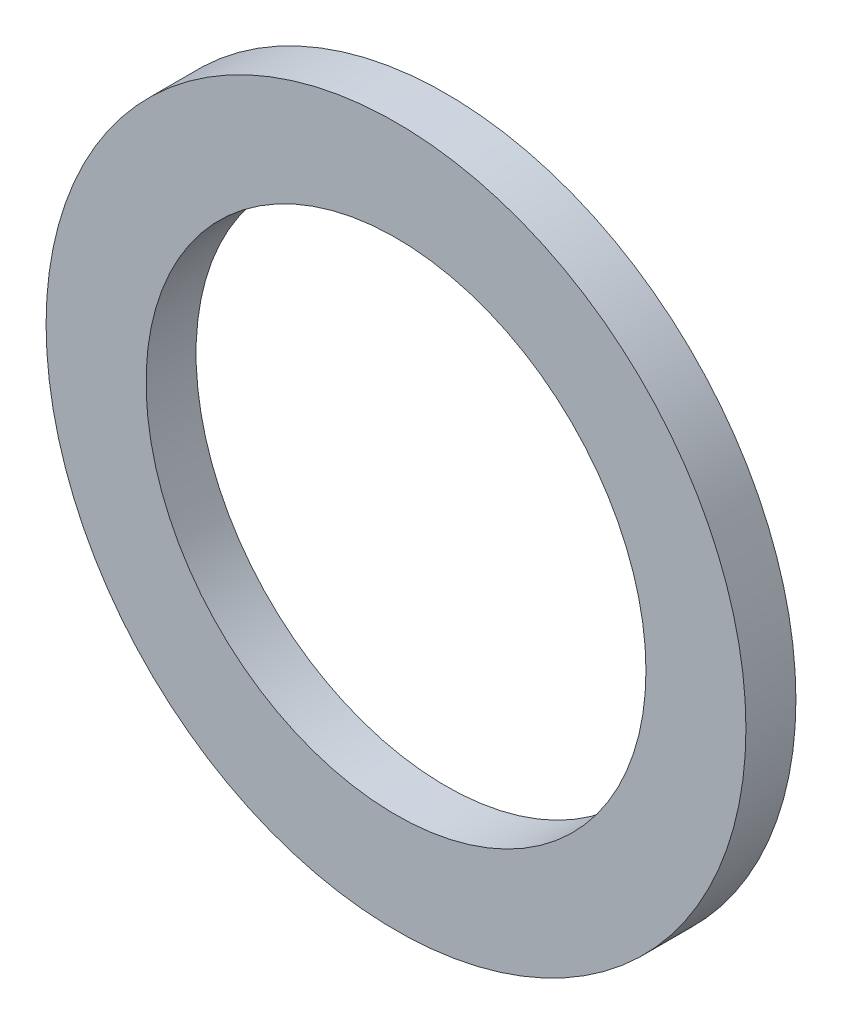
SolidWorks part; units mm, degrees
ref_plane "前视基准面" through (0, 0, 0) normal (0, 0, 1) x (1, 0, 0)
ref_plane "上视基准面" through (0, 0, 0) normal (0, 1, 0) x (1, 0, 0)
ref_plane "右视基准面" through (0, 0, 0) normal (1, 0, 0) x (0, 0, -1)
sketch "草图1" plane through (0, 0, 0) normal (0, 0, 1) x (1, 0, 0)
  circle A0 centre (0, 0) radius 25
  circle A1 centre (0, 0) radius 35
  dimension "D1" = 70
  dimension "D2" = 50
extrude "凸台-拉伸1" add sketch "草图1" along normal blind 5
